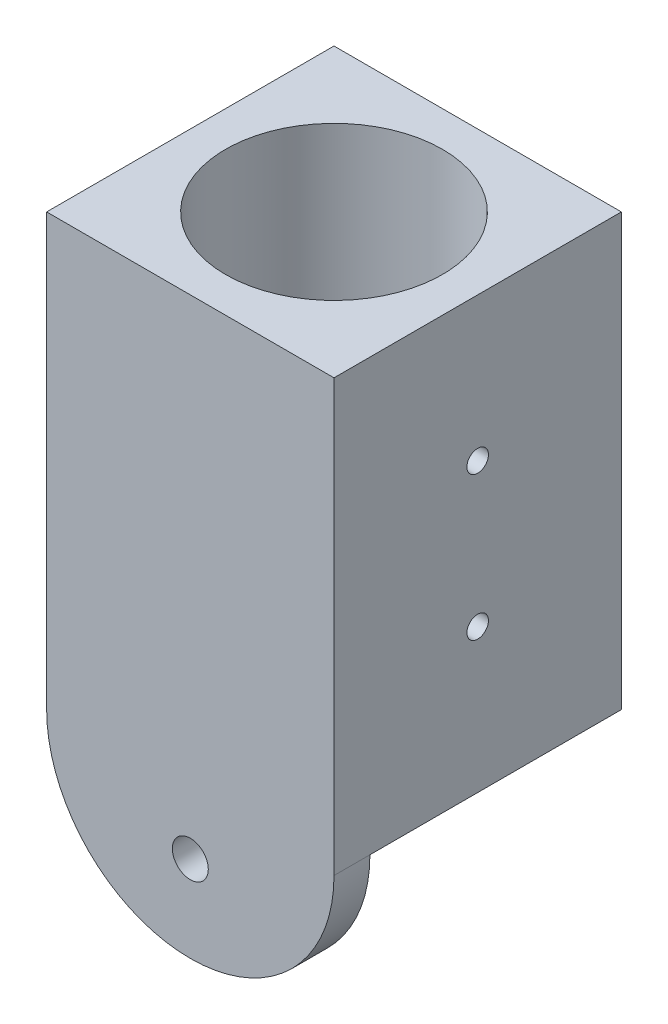
SolidWorks part; units mm, degrees
ref_plane "前基準面" through (0, 0, 0) normal (0, 0, 1) x (1, 0, 0)
ref_plane "上基準面" through (0, 0, 0) normal (0, 1, 0) x (1, 0, 0)
ref_plane "右基準面" through (0, 0, 0) normal (1, 0, 0) x (0, 0, -1)
sketch "草圖1" plane through (0, 0, 0) normal (0, 1, 0) x (1, 0, 0)
  line L1 (-20, 20) -> (20, 20)
  line L2 (-20, 20) -> (-20, -20)
  line L3 (-20, -20) -> (20, -20)
  line L4 (20, 20) -> (20, -20)
  line L5 (-20, 20) -> (20, -20) construction
  line L6 (-20, -20) -> (20, 20) construction
  dimension "D2" = 40
extrude "填料-伸長1" add sketch "草圖1" along normal blind 60
sketch "草圖2" plane through (0, 60, 0) normal (0, 1, 0) x (1, 0, 0)
  circle A0 centre (0, 0) radius 15.1
  dimension "D1" = 30.2
extrude "除料-伸長1" cut sketch "草圖2" against normal blind 50
sketch "草圖3" plane through (0, 0, 20) normal (0, 0, 1) x (1, 0, 0)
  line L0 (-20, 0) -> (20, 0)
  arc A0 (-20, 0) -> (20, 0) centre (0, 0) ccw
  circle A1 centre (0, -8) radius 2.5
  dimension "D1" = 5
  dimension "D2" = 8
extrude "填料-伸長2" add sketch "草圖3" against normal blind 5
sketch "草圖4" plane through (20, 0, 0) normal (1, 0, 0) x (0, 0, -1)
  circle A0 centre (0, 20) radius 1.5
  dimension "D1" = 3
  dimension "D2" = 20
extrude "除料-伸長2" cut sketch "草圖4" against normal through all
pattern_linear "直線複製排列1" count 2 spacing 20 along (0, 1, 0) of "除料-伸長2"
